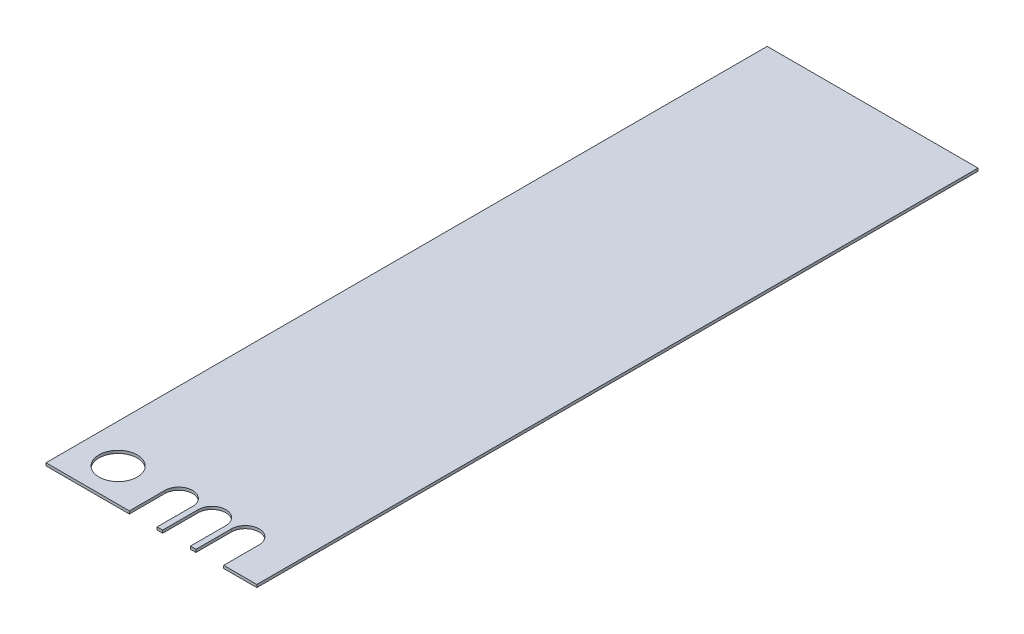
SolidWorks part; units mm, degrees
material "Polyurethane Foam Rigid"
ref_plane "Front Plane" through (0, 0, 0) normal (0, 0, 1) x (1, 0, 0)
ref_plane "Top Plane" through (0, 0, 0) normal (0, 1, 0) x (1, 0, 0)
ref_plane "Right Plane" through (0, 0, 0) normal (1, 0, 0) x (0, 0, -1)
sketch "Sketch1" plane through (0, 0, 0) normal (0, 1, 0) x (1, 0, 0)
  line L1 (-241.3, -825.5) -> (241.3, -825.5)
  line L2 (-241.3, -825.5) -> (-241.3, 825.5)
  line L3 (-241.3, 825.5) -> (241.3, 825.5)
  line L4 (241.3, -825.5) -> (241.3, 825.5)
  line L5 (-241.3, -825.5) -> (241.3, 825.5) construction
  line L6 (-241.3, 825.5) -> (241.3, -825.5) construction
  point P0 (0, 0)
  dimension "D1" = 1651
  dimension "D2" = 482.6
extrude "Boss-Extrude1" add sketch "Sketch1" along normal blind 6.35
sketch "Sketch2" plane through (0, 6.35, 0) normal (0, 1, 0) x (1, 0, 0)
  circle A0 centre (-152.4, -749.3) radius 43.9236
  dimension "D1" = 87.8473
extrude "Cut-Extrude1" cut sketch "Sketch2" against normal through all
sketch "Sketch3" plane through (0, 6.35, 0) normal (0, 1, 0) x (1, 0, 0)
  circle A0 centre (146.6535, 668.2602) radius 57.15
  dimension "D1" = 114.3
extrude "Cut-Extrude2" [suppressed] cut sketch "Sketch3" against normal through all
sketch "Sketch4" plane through (0, 0, 0) normal (0, -1, 0) x (1, 0, 0)
  line L0 (-50.4445, 744.2936) -> (-50.4445, 825.5)
  line L1 (-241.3, 825.5) -> (241.3, 825.5) construction
  line L2 (-50.4445, 825.5) -> (13.0555, 825.5)
  line L3 (13.0555, 825.5) -> (13.0555, 744.2936)
  line L4 (25.7555, 744.2936) -> (25.7555, 825.5)
  line L5 (25.7555, 825.5) -> (89.2555, 825.5)
  line L6 (89.2555, 825.5) -> (89.2555, 744.2936)
  line L7 (101.9555, 744.2936) -> (101.9555, 825.5)
  line L8 (101.9555, 825.5) -> (165.4555, 825.5)
  line L9 (165.4555, 825.5) -> (165.4555, 744.2936)
  arc A0 (-50.4445, 744.2936) -> (13.0555, 744.2936) centre (-18.6945, 744.2936) ccw
  arc A1 (25.7555, 744.2936) -> (89.2555, 744.2936) centre (57.5055, 744.2936) ccw
  arc A2 (101.9555, 744.2936) -> (165.4555, 744.2936) centre (133.7055, 744.2936) ccw
  dimension "D1" = 31.75
extrude "Cut-Extrude3" cut sketch "Sketch4" against normal through all
sketch "Sketch5" plane through (0, 6.35, 0) normal (0, 1, 0) x (1, 0, 0)
  line L0 (-105.6446, 754.5064) -> (-105.6446, 825.5)
  line L1 (241.3, 825.5) -> (-241.3, 825.5) construction
  line L2 (-105.6446, 825.5) -> (-241.3, 825.5)
  line L3 (-241.3, 825.5) -> (-241.3, 706.8462)
  line L4 (-241.3, 825.5) -> (-241.3, -825.5) construction
  arc A0 (-241.3, 706.8462) -> (-105.6446, 754.5064) centre (-181.8446, 754.5064) ccw
  dimension "D1" = 152.4
  dimension "D2" = 754.5064
  dimension "D3" = 181.8446
extrude "Cut-Extrude4" [suppressed] cut sketch "Sketch5" against normal through all
fillet "Fillet1" [suppressed] radius 7.62
